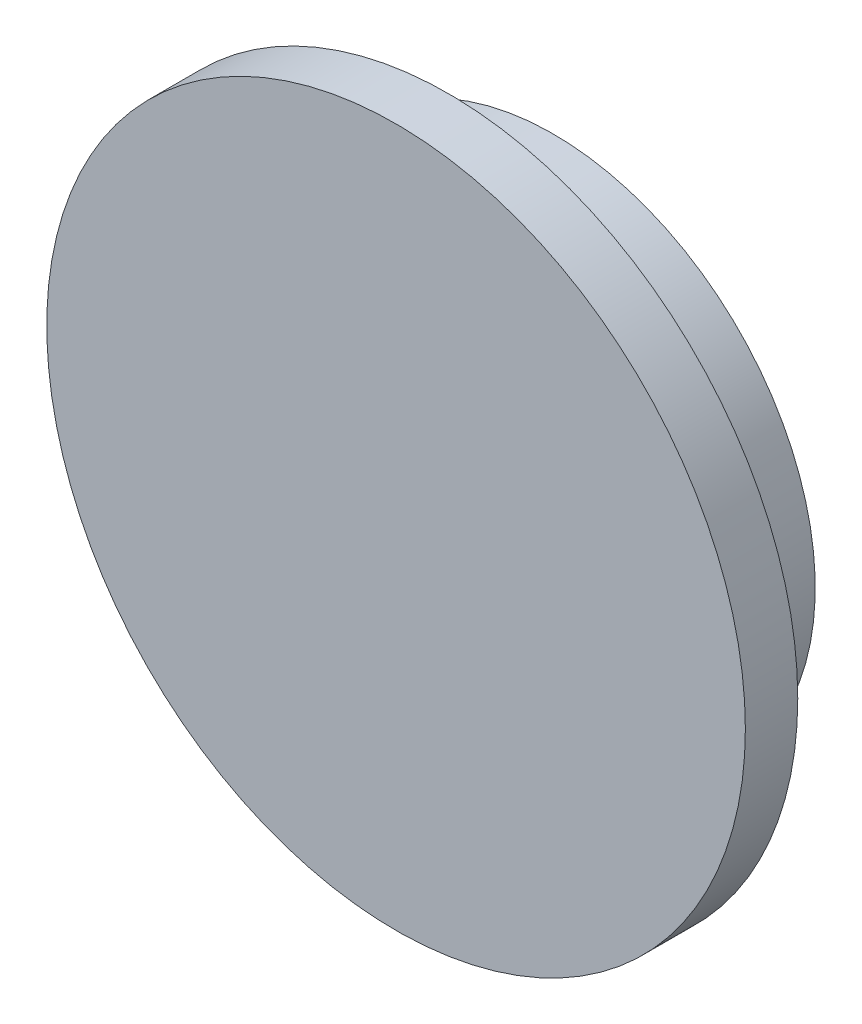
SolidWorks part; units mm, degrees
ref_plane "前视基准面" through (0, 0, 0) normal (0, 0, 1) x (1, 0, 0)
ref_plane "上视基准面" through (0, 0, 0) normal (0, 1, 0) x (1, 0, 0)
ref_plane "右视基准面" through (0, 0, 0) normal (1, 0, 0) x (0, 0, -1)
sketch "草图1" plane through (0, 0, 0) normal (0, 0, 1) x (1, 0, 0)
  circle A0 centre (0, 0) radius 200
extrude "凸台-拉伸3" add sketch "草图1" along normal blind 30
sketch "草图3" plane through (0, 0, 0) normal (0, 0, -1) x (-1, 0, 0)
  circle A0 centre (0, 0) radius 150
extrude "凸台-拉伸4" add sketch "草图3" along normal blind 60
sketch "草图4" plane through (0, 0, -60) normal (0, 0, -1) x (-1, 0, 0)
  circle A0 centre (0, 0) radius 48
extrude "切除-拉伸1" cut sketch "草图4" against normal blind 45
